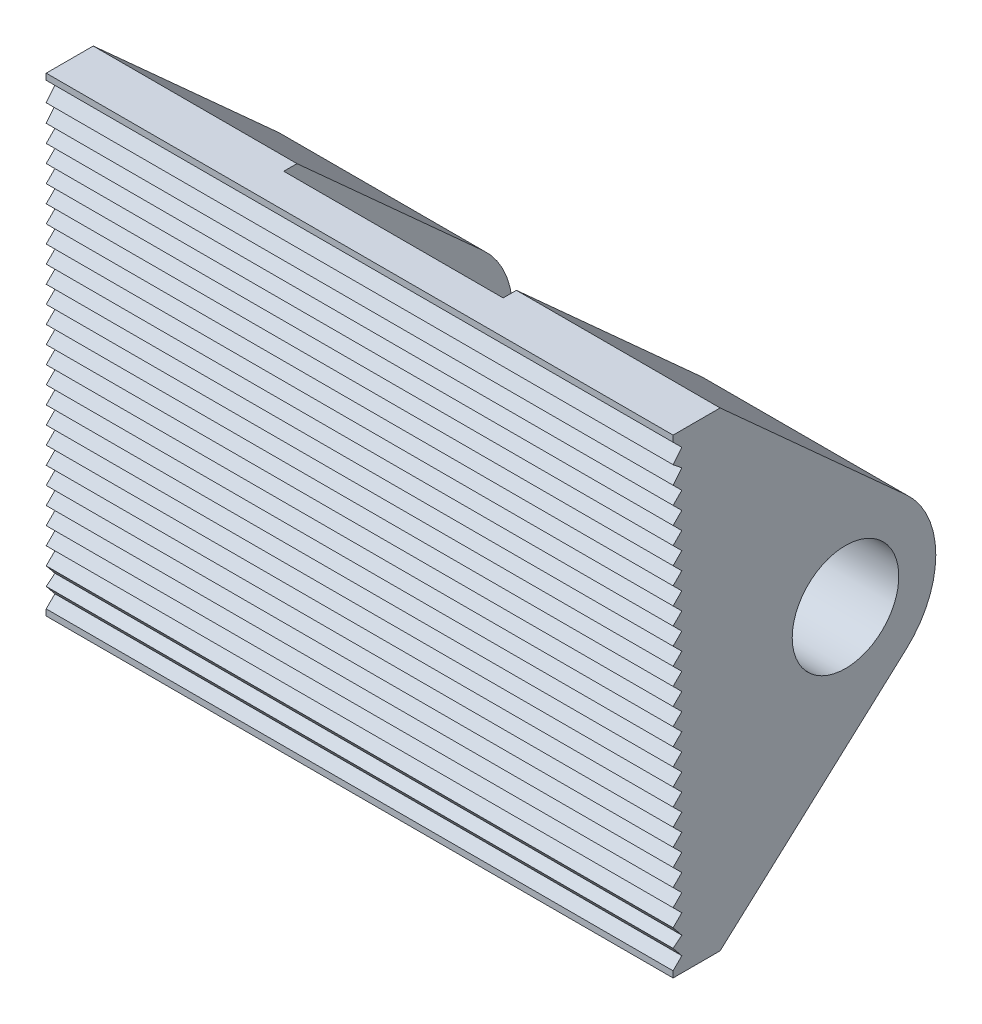
SolidWorks part; units mm, degrees
ref_plane "Plan de face" through (0, 0, 0) normal (0, 0, 1) x (1, 0, 0)
ref_plane "Plan de dessus" through (0, 0, 0) normal (0, 1, 0) x (1, 0, 0)
ref_plane "Plan de droite" through (0, 0, 0) normal (1, 0, 0) x (0, 0, -1)
sketch "Esquisse2" plane through (0, 0, 0) normal (0, 0, 1) x (1, 0, 0)
  line L1 (-10, -7.5) -> (10, -7.5)
  line L2 (-10, -7.5) -> (-10, 7.5)
  line L3 (-10, 7.5) -> (10, 7.5)
  line L4 (10, -7.5) -> (10, 7.5)
  line L5 (-10, -7.5) -> (10, 7.5) construction
  line L6 (-10, 7.5) -> (10, -7.5) construction
  point P0 (0, 0)
  dimension "D1" = 20
  dimension "D2" = 15
extrude "Boss.-Extru.1" add sketch "Esquisse2" along normal blind 1.5
sketch "Esquisse3" plane through (-10, 0, 0) normal (-1, 0, 0) x (0, 0, 1)
  line L0 (-5.9319, 2.1367) -> (0, 7.5)
  line L1 (-5.9319, -2.1367) -> (0, -7.5)
  line L2 (0, 7.5) -> (0, -7.5) construction
  line L5 (0, 7.5) -> (0, -7.5)
  circle A0 centre (-4, 0) radius 1.7
  arc A1 (-5.9319, 2.1367) -> (-5.9319, -2.1367) centre (-4, 0) ccw
  line M2 (0, 7.5) -> (0, -7.5)
  dimension "D2" = 4
extrude "Boss.-Extru.2" add sketch "Esquisse3" against normal blind 20 contours L0 A1 L1 A0 M2
sketch "Esquisse4" plane through (-10, 0, 0) normal (-1, 0, 0) x (0, 0, 1)
  line L0 (0, 0) -> (1.5, 0) construction
  line L1 (1.5, 7.5) -> (1.5, -7.5) construction
  line L2 (1.5, 0) -> (1.2221, -0.2779)
  line L3 (1.2221, -0.2779) -> (1.5, -0.5558)
  line L4 (1.2221, -0.2779) -> (1.2221, -7.5) construction
  line L5 (1.5, -7.5) -> (0, -7.5) construction
  line L6 (1.5, -0.5558) -> (1.2221, -0.8337)
  line L7 (1.2221, -0.8337) -> (1.5, -1.1116)
  line L8 (1.5, -1.1116) -> (1.2221, -1.3894)
  line L9 (1.2221, -1.3894) -> (1.5, -1.6673)
  line L10 (1.5, -1.6673) -> (1.2221, -1.9452)
  line L11 (1.2221, -1.9452) -> (1.5, -2.2231)
  line L12 (1.5, -2.2231) -> (1.2221, -2.501)
  line L13 (1.2221, -2.501) -> (1.5, -2.7789)
  line L14 (1.5, -2.7789) -> (1.2221, -3.0568)
  line L15 (1.2221, -3.0568) -> (1.5, -3.3347)
  line L29 (1.5, -3.3347) -> (1.2221, -3.6126)
  line L30 (1.2221, -3.6126) -> (1.5, -3.8904)
  line L31 (1.5, -3.8904) -> (1.2221, -4.1683)
  line L32 (1.2221, -4.1683) -> (1.5, -4.4462)
  line L33 (1.5, -4.4462) -> (1.2221, -4.7241)
  line L34 (1.2221, -4.7241) -> (1.5, -5.002)
  line L35 (1.5, -5.002) -> (1.2221, -5.2799)
  line L36 (1.2221, -5.2799) -> (1.5, -5.5578)
  line L37 (1.5, -5.5578) -> (1.2221, -5.8357)
  line L38 (1.2221, -5.8357) -> (1.5, -6.1136)
  line L39 (1.5, -6.1136) -> (1.2221, -6.4558)
  line L40 (1.2221, -6.4558) -> (1.5, -6.6814)
  line L41 (1.5, -6.6814) -> (1.2221, -7.0236)
  line L42 (1.2221, -7.0236) -> (1.5, -7.3015)
  line L43 (1.5, 7.3015) -> (1.5, -7.3015)
  line L44 (1.2221, 7.0236) -> (1.5, 7.3015)
  line L45 (1.5, 6.6814) -> (1.2221, 7.0236)
  line L46 (1.2221, 6.4558) -> (1.5, 6.6814)
  line L47 (1.5, 6.1136) -> (1.2221, 6.4558)
  line L48 (1.2221, 5.8357) -> (1.5, 6.1136)
  line L49 (1.5, 5.5578) -> (1.2221, 5.8357)
  line L50 (1.2221, 5.2799) -> (1.5, 5.5578)
  line L51 (1.5, 5.002) -> (1.2221, 5.2799)
  line L52 (1.2221, 4.7241) -> (1.5, 5.002)
  line L53 (1.5, 4.4462) -> (1.2221, 4.7241)
  line L54 (1.2221, 4.1683) -> (1.5, 4.4462)
  line L55 (1.5, 3.8904) -> (1.2221, 4.1683)
  line L56 (1.2221, 3.6126) -> (1.5, 3.8904)
  line L57 (1.5, 3.3347) -> (1.2221, 3.6126)
  line L58 (1.2221, 3.0568) -> (1.5, 3.3347)
  line L59 (1.5, 2.7789) -> (1.2221, 3.0568)
  line L60 (1.2221, 2.501) -> (1.5, 2.7789)
  line L61 (1.5, 2.2231) -> (1.2221, 2.501)
  line L62 (1.2221, 1.9452) -> (1.5, 2.2231)
  line L63 (1.5, 1.6673) -> (1.2221, 1.9452)
  line L64 (1.2221, 1.3894) -> (1.5, 1.6673)
  line L65 (1.5, 1.1116) -> (1.2221, 1.3894)
  line L66 (1.2221, 0.8337) -> (1.5, 1.1116)
  line L67 (1.5, 0.5558) -> (1.2221, 0.8337)
  line L68 (1.2221, 0.2779) -> (1.5, 0.5558)
  line L69 (1.5, 0) -> (1.2221, 0.2779)
  line M19 (1.5, -7.5) -> (1.5, 7.5)
ref_plane "Plan1" through (0, 0, 0) normal (-1, 0, 0) x (0, 0, 1)
sketch "Esquisse5" plane through (0, 0, 0) normal (-1, 0, 0) x (0, 0, 1)
  line L0 (0.4216, 7.5) -> (0.4216, -7.5)
  line L1 (1.5, 7.5) -> (0, 7.5) construction
  line L2 (1.5, -7.5) -> (0, -7.5) construction
  line L3 (0.4216, 7.5) -> (0, 7.5)
  line L4 (0.4216, -7.5) -> (0, -7.5)
  line L54 (1.5, -7.5) -> (1.5, 7.5)
  line L55 (1.5, 7.5) -> (0, 7.5)
  line L57 (-5.9319, -2.1367) -> (0, -7.5)
  line L58 (0, -7.5) -> (1.5, -7.5)
  line L87 (-5.9319, -2.1367) -> (0, -7.5)
  line L95 (0, 7.5) -> (-5.9319, 2.1367)
  line L96 (0, 7.5) -> (-5.9319, 2.1367)
  arc A6 (-5.9319, 2.1367) -> (-5.9319, -2.1367) centre (-4, 0) ccw
  arc A7 (-5.9319, 2.1367) -> (-5.9319, -2.1367) centre (-4, 0) ccw
  point P1 (0, 0)
  point P2 (-2, 0)
  point P3 (-2, 0)
  point P4 (0, 0)
  point P5 (0, 0)
  point P7 (-2, 0)
  point P9 (0, 0)
  point P18 (-12.5535, -2.5858)
  dimension "D1" = 0
extrude "Enlèv. mat.-Extru.2" cut sketch "Esquisse5" against normal mid plane 7
extrude "Enlèv. mat.-Extru.4" cut sketch "Esquisse4" against normal blind 21 contours L45 L43 L44 | L47 L43 L46 | L49 L43 L48 | L51 L43 L50 | L53 L43 L52 | L55 L43 L54 | L57 L43 L56 | L59 L43 L58 | L61 L43 L60 | L63 L43 L62 | L65 L43 L64 | L67 L43 L66 | L69 L68 M19 | L2 L3 M19 | L6 L7 M19 | L8 L9 M19 | L10 L11 M19 | L12 L13 M19 | L14 L15 M19 | L29 L30 M19 | L31 L32 M19 | L33 L34 M19 | L35 L36 M19 | L37 L38 M19 | L39 L40 M19 | L41 L42 M19
